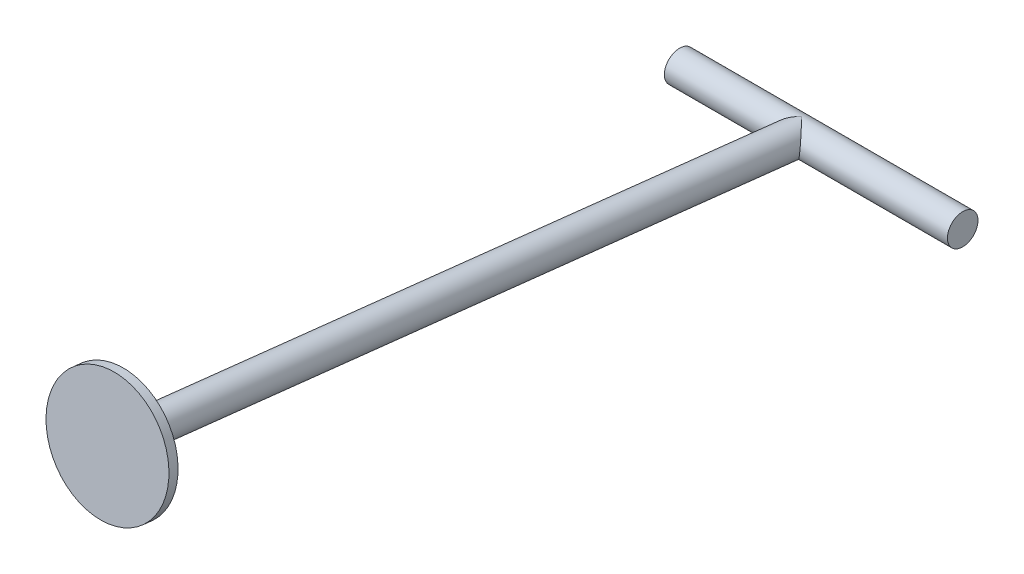
SolidWorks part; units mm, degrees
material "Aleación 1060"
ref_plane "Alzado" through (0, 0, 0) normal (0, 0, 1) x (1, 0, 0)
ref_plane "Planta" through (0, 0, 0) normal (0, 1, 0) x (1, 0, 0)
ref_plane "Vista lateral" through (0, 0, 0) normal (1, 0, 0) x (0, 0, -1)
ref_plane "Plano3" through (-202.7462, 0, 0) normal (1, 0, 0) x (0, 0, -1)
sketch "Croquis3" plane through (-202.7462, 0, 0) normal (1, 0, 0) x (0, 0, -1)
  circle A0 centre (-5751.601, 1500.1907) radius 25
  dimension "D1" = 50
extrude "Saliente-Extruir1" add sketch "Croquis3" against normal up to surface (463.3 mm away)
ref_plane "Plano5" through (0, 775.9667, 6979.1474) normal (0, -0.1105, -0.9939) x (1, 0, 0)
sketch "Croquis5" plane through (0, 775.9667, 6979.1474) normal (0, -0.1105, -0.9939) x (1, 0, 0)
  circle A0 centre (-469.3962, -855.4359) radius 100
  dimension "D1" = 200
extrude "Saliente-Extruir2" add sketch "Croquis5" along normal blind 15 separate body
sketch "Croquis6" plane through (0, 774.3091, 6964.2393) normal (0, -0.1105, -0.9939) x (1, 0, 0)
  circle A0 centre (-469.3962, -855.4359) radius 25
  dimension "D1" = 50
extrude "Saliente-Extruir3" add sketch "Croquis6" along normal up to next
